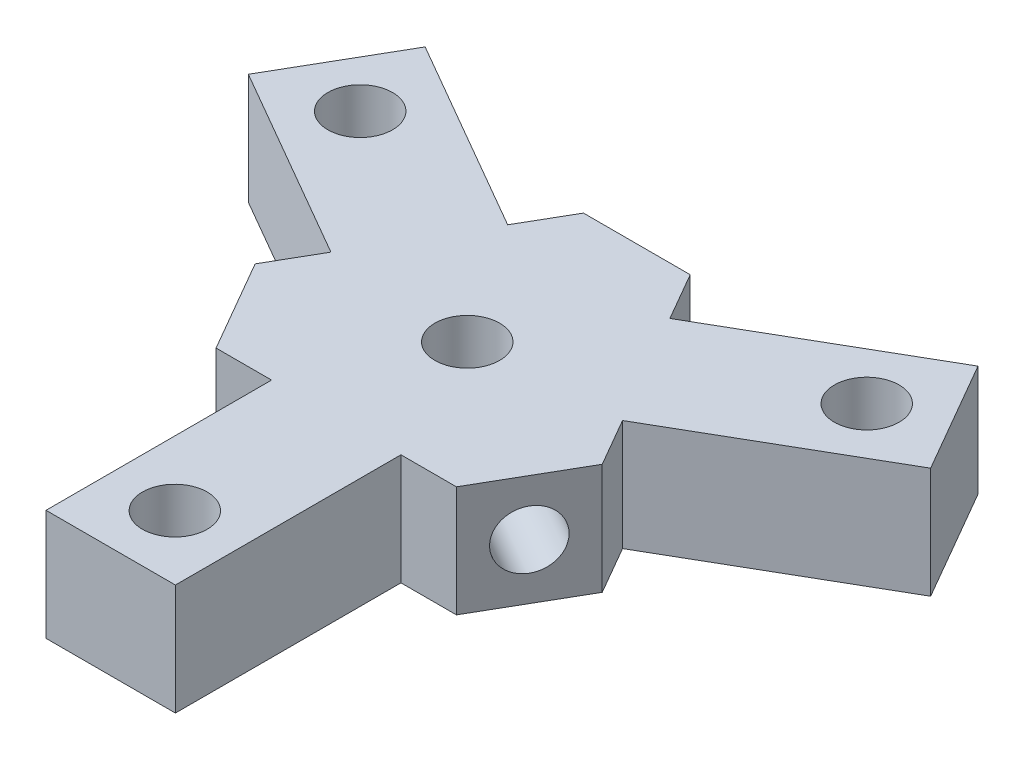
SolidWorks part; units mm, degrees
ref_plane "Front Plane" through (0, 0, 0) normal (0, 0, 1) x (1, 0, 0)
ref_plane "Top Plane" through (0, 0, 0) normal (0, 1, 0) x (1, 0, 0)
ref_plane "Right Plane" through (0, 0, 0) normal (1, 0, 0) x (0, 0, -1)
sketch "Sketch1" plane through (0, 0, 0) normal (0, 1, 0) x (1, 0, 0)
  line L1 (0, 18) -> (-15.5885, -9)
  line L2 (-15.5885, -9) -> (15.5885, -9)
  line L3 (15.5885, -9) -> (0, 18)
  line L4 (-10, 11.65) -> (10, 11.65)
  line L5 (-10, 11.65) -> (-10, 24.35)
  line L6 (-10, 24.35) -> (10, 24.35)
  line L7 (10, 11.65) -> (10, 24.35)
  line L8 (-10, 11.65) -> (10, 24.35) construction
  line L9 (-10, 24.35) -> (10, 11.65) construction
  line L17 (26.0877, -3.5147) -> (16.0877, -20.8353)
  line L18 (5.0892, -14.4853) -> (16.0877, -20.8353)
  line L19 (15.0892, 2.8353) -> (5.0892, -14.4853)
  line L21 (-6, 13) -> (6, 13)
  line L23 (-6, 23) -> (6, 23)
  line L25 (-6, 13) -> (6, 23) construction
  line L26 (-6, 23) -> (6, 13) construction
  line L30 (15.0892, 2.8353) -> (26.0877, -3.5147)
  line L31 (-16.0877, -20.8353) -> (-26.0877, -3.5147)
  line L32 (-15.0892, 2.8353) -> (-26.0877, -3.5147)
  line L33 (-5.0892, -14.4853) -> (-15.0892, 2.8353)
  line L34 (-5.0892, -14.4853) -> (-16.0877, -20.8353)
  circle A0 centre (0, 0) radius 9 construction
  circle A1 centre (0, 0) radius 2.2225
  dimension "D1" = 18
  dimension "D2" = 3
  dimension "D3" = 20
  dimension "D4" = 12.7
extrude "Boss-Extrude2" add sketch "Sketch1" along normal blind 7.62 contours L33 L2 L19 L3 L4 L1
sketch "Sketch2" plane through (-10.0892, 0, 5.825) normal (-0.866, 0, 0.5) x (0.5, 0, 0.866)
  line L0 (-3.6662, 3.81) -> (3.6662, 3.81)
  line L1 (-3.6662, 7.62) -> (-3.6662, 0) construction
  line L2 (3.6662, 7.62) -> (3.6662, 0) construction
  line L3 (3.6662, 3.81) -> (0, 7.62)
  line L4 (3.6662, 7.62) -> (-3.6662, 7.62) construction
  line L5 (0, 7.62) -> (0, 0)
  line L6 (3.6662, 0) -> (-3.6662, 0) construction
  circle A0 centre (0, 3.81) radius 2
extrude "Cut-Extrude1" cut sketch "Sketch2" against normal blind 6.35 contours L5 A0 L0 | L0 A0 L5 | L5 A0 L0 | L0 A0 L5
sketch "Sketch3" plane through (10.0892, 0, 5.825) normal (0.866, 0, 0.5) x (0.5, 0, -0.866)
  line L0 (0, 7.62) -> (0, 0)
  line L1 (3.6662, 7.62) -> (-3.6662, 7.62) construction
  line L2 (3.6662, 0) -> (-3.6662, 0) construction
  line L3 (-3.6662, 3.81) -> (3.6662, 3.81)
  line L4 (-3.6662, 7.62) -> (-3.6662, 0) construction
  line L5 (3.6662, 7.62) -> (3.6662, 0) construction
  circle A0 centre (0, 3.81) radius 2
extrude "Cut-Extrude7" cut sketch "Sketch3" against normal blind 6.35 contours L3 A0 L0 | L0 A0 L3 | L3 A0 L0 | L0 A0 L3
sketch "Sketch4" plane through (0, 0, -11.65) normal (0, 0, -1) x (-1, 0, 0)
  line L0 (0, 7.62) -> (0, 0)
  line L1 (3.6662, 7.62) -> (-3.6662, 7.62) construction
  line L2 (3.6662, 0) -> (-3.6662, 0) construction
  line L3 (-3.6662, 3.81) -> (3.6662, 3.81)
  line L4 (-3.6662, 7.62) -> (-3.6662, 0) construction
  line L5 (3.6662, 7.62) -> (3.6662, 0) construction
  circle A0 centre (0, 3.81) radius 2
extrude "Cut-Extrude8" cut sketch "Sketch4" against normal blind 6.35 contours L3 A0 L0 | L0 A0 L3 | L3 A0 L0 | L0 A0 L3
sketch "Sketch5" plane through (0, 0, 0) normal (0, -1, 0) x (1, 0, 0)
  line L0 (-8.2561, 9) -> (8.2561, 9) construction
  line L1 (-4.445, 2.65) -> (4.445, 2.65)
  line L2 (-4.445, 2.65) -> (-4.445, 15.35)
  line L3 (-4.445, 15.35) -> (4.445, 15.35)
  line L4 (4.445, 2.65) -> (4.445, 15.35)
  line L5 (-4.445, 2.65) -> (4.445, 15.35) construction
  line L6 (-4.445, 15.35) -> (4.445, 2.65) construction
  line L7 (15.516, -3.8255) -> (11.071, -11.5245)
  line L8 (4.5175, 2.5245) -> (15.516, -3.8255)
  line L9 (0.0725, -5.1745) -> (11.071, -11.5245)
  line L10 (4.5175, 2.5245) -> (0.0725, -5.1745)
  line L11 (-11.071, -11.5245) -> (-15.516, -3.8255)
  line L12 (-0.0725, -5.1745) -> (-11.071, -11.5245)
  line L13 (-4.5175, 2.5245) -> (-15.516, -3.8255)
  line L14 (-0.0725, -5.1745) -> (-4.5175, 2.5245)
  line L15 (11.071, -11.5245) -> (18.9899, -16.0965)
  line L16 (-4.445, 15.35) -> (4.445, 15.35)
  line L17 (-4.445, 15.35) -> (-4.445, 24.494)
  line L18 (-4.445, 24.494) -> (4.445, 24.494)
  line L19 (4.445, 15.35) -> (4.445, 24.494)
  line L20 (23.4349, -8.3975) -> (18.9899, -16.0965)
  line L21 (15.516, -3.8255) -> (23.4349, -8.3975)
  line L22 (-15.516, -3.8255) -> (-23.4349, -8.3975)
  line L23 (-18.9899, -16.0965) -> (-23.4349, -8.3975)
  line L24 (-11.071, -11.5245) -> (-18.9899, -16.0965)
  circle A0 centre (0, 20.09) radius 2.2225
  circle A1 centre (17.3985, -10.045) radius 2.2225
  circle A2 centre (-17.3985, -10.045) radius 2.2225
  point P0 (0, 9)
  line M5 (-11.9223, 2.65) -> (-3.6662, -11.65)
  line M7 (3.6662, -11.65) -> (11.9223, 2.65)
  line M9 (8.2561, 9) -> (-8.2561, 9)
  dimension "D6" = 20.09
  dimension "D1" = 8.89
  dimension "D2" = 12.7
  dimension "D4" = 9.144
  dimension "D3" = 3
  dimension "D5" = 3
  dimension "D7" = 3
extrude "Boss-Extrude3" add sketch "Sketch5" against normal blind 7.62 contours L3 L19 L18 L17 | L4 L3 L2 M9 | L9 L7 L8 M7 | L21 L7 L15 L20 | L13 L11 L12 M5 | L24 L11 L22 L23
